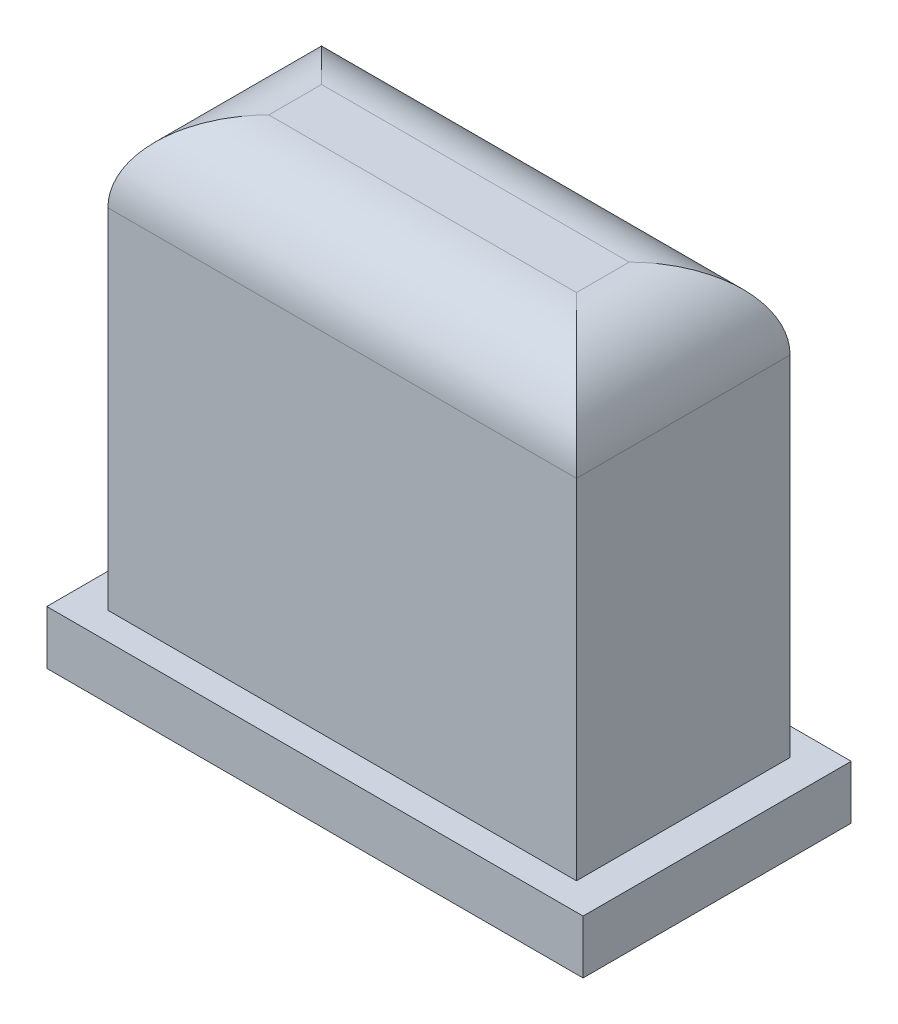
SolidWorks part; units mm, degrees
ref_plane "Alzado" through (0, 0, 0) normal (0, 0, 1) x (1, 0, 0)
ref_plane "Planta" through (0, 0, 0) normal (0, 1, 0) x (1, 0, 0)
ref_plane "Vista lateral" through (0, 0, 0) normal (1, 0, 0) x (0, 0, -1)
sketch "Croquis1" plane through (0, 0, 0) normal (0, 1, 0) x (1, 0, 0)
  line L1 (-50, -25) -> (50, -25)
  line L2 (-50, -25) -> (-50, 25)
  line L3 (-50, 25) -> (50, 25)
  line L4 (50, -25) -> (50, 25)
  line L5 (-50, -25) -> (50, 25) construction
  line L6 (-50, 25) -> (50, -25) construction
  point P0 (0, 0)
  dimension "D1" = 50
  dimension "D2" = 100
extrude "Saliente-Extruir1" add sketch "Croquis1" along normal blind 10
sketch "Croquis2" plane through (0, 10, 0) normal (0, 1, 0) x (1, 0, 0)
  line L1 (43.6902, -19.9188) -> (-43.6902, -19.9188)
  line L2 (43.6902, -19.9188) -> (43.6902, 19.9188)
  line L3 (43.6902, 19.9188) -> (-43.6902, 19.9188)
  line L4 (-43.6902, -19.9188) -> (-43.6902, 19.9188)
  line L5 (43.6902, -19.9188) -> (-43.6902, 19.9188) construction
  line L6 (43.6902, 19.9188) -> (-43.6902, -19.9188) construction
  point P0 (0, 0)
extrude "Saliente-Extruir2" add sketch "Croquis2" along normal blind 80
fillet "Redondeo1" radius 15 4 edges at (-43.6902, 90, 0) (0, 90, -19.9188) (43.6902, 90, 0) (0, 90, 19.9188)
sketch "Croquis3" plane through (0, 0, 0) normal (0, -1, 0) x (1, 0, 0)
  circle A0 centre (0, 0) radius 6.0824
extrude "Saliente-Extruir3" add sketch "Croquis3" along normal blind 10
